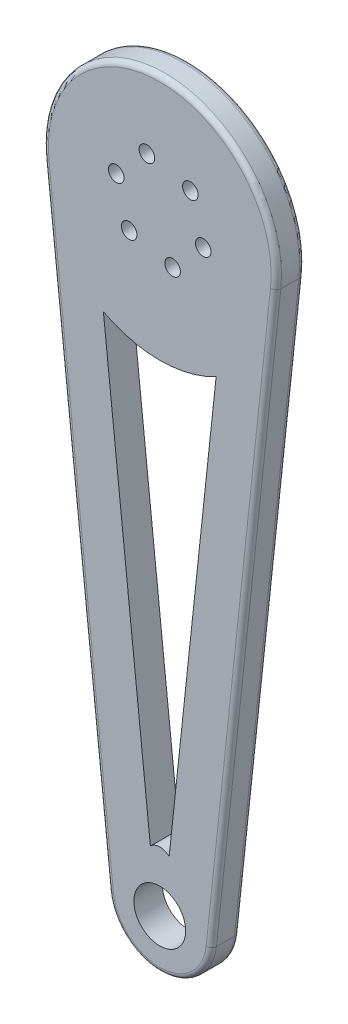
SolidWorks part; units mm, degrees
ref_plane "前视基准面" through (0, 0, 0) normal (0, 0, 1) x (1, 0, 0)
ref_plane "上视基准面" through (0, 0, 0) normal (0, 1, 0) x (1, 0, 0)
ref_plane "右视基准面" through (0, 0, 0) normal (1, 0, 0) x (0, 0, -1)
sketch "草图1" plane through (0, 0, 0) normal (0, 0, 1) x (1, 0, 0)
  line L1 (-44.7446, -4.7872) -> (-19.8865, -237.1277)
  line L2 (44.7446, -4.7872) -> (19.8865, -237.1277)
  arc A2 (-44.7446, -4.7872) -> (44.7446, -4.7872) centre (0, 0) cw
  arc A3 (-19.8865, -237.1277) -> (19.8865, -237.1277) centre (0, -235) ccw
extrude "凸台-拉伸1" add sketch "草图1" along normal blind 11
sketch "草图2" plane through (0, 0, 0) normal (0, 0, -1) x (-1, 0, 0)
  line L0 (0, 0) -> (0, -95.701) construction
  circle A0 centre (0, -235.836) radius 10
extrude "切除-拉伸1" cut sketch "草图2" against normal blind 11
fillet "圆角1" radius 2 8 edges at (0, 45, 11) (0, -255, 11) (32.3156, -120.9574, 11) (-32.3156, -120.9574, 11) (0, -255, 0) (-32.3156, -120.9574, 0) (0, 45, 0) (32.3156, -120.9574, 0)
sketch "草图3" plane through (0, 0, 11) normal (0, 0, 1) x (1, 0, 0)
  circle A0 centre (0, -235.836) radius 10
sketch "草图4" plane through (0, 0, 0) normal (0, 0, -1) x (-1, 0, 0)
  line L0 (0, 0) -> (0, -235.836) construction
  line L1 (-21.7598, -44.6823) -> (-3.626, -214.173)
  line L3 (21.7598, -44.6823) -> (3.6153, -214.2726)
  line L4 (17.8979, -236.9149) -> (42.756, -4.5745) construction
  line L5 (-42.756, -4.5745) -> (-17.8979, -236.9149) construction
  arc A2 (21.7598, -44.6823) -> (-21.7598, -44.6823) centre (0, -3.3509) cw
  arc A3 (-3.626, -214.173) -> (3.6153, -214.2726) centre (-0.0551, -217.8435) cw
  point P7 (0, -44.6823)
extrude "切除-拉伸2" cut sketch "草图4" against normal blind 20
sketch "草图6" plane through (0, 0, 11) normal (0, 0, 1) x (1, 0, 0)
  circle A0 centre (-16.7892, 3.9603) radius 2
  circle A1 centre (-4.9649, 16.52) radius 2
  circle A2 centre (11.8243, 12.5598) radius 2
  circle A3 centre (16.7892, -3.9603) radius 2
  circle A4 centre (4.9649, -16.52) radius 2
  circle A5 centre (-11.8243, -12.5598) radius 2
  point P15 (0, 0)
  dimension "D1" = 6
  dimension "D2" = 17.25
extrude "切除-拉伸4" cut sketch "草图6" against normal blind 33
sketch "草图7" plane through (0, 0, 11) normal (0, 0, 1) x (1, 0, 0)
  circle A0 centre (-4.9649, 16.52) radius 3
  circle A1 centre (11.8243, 12.5598) radius 3
  circle A2 centre (16.7892, -3.9603) radius 3
  circle A3 centre (4.9649, -16.52) radius 3
  circle A4 centre (-11.8243, -12.5598) radius 3
  circle A5 centre (-16.7892, 3.9603) radius 3
  point P15 (0, 0)
  dimension "D1" = 6
extrude "切除-拉伸5" cut sketch "草图7" against normal blind 5
